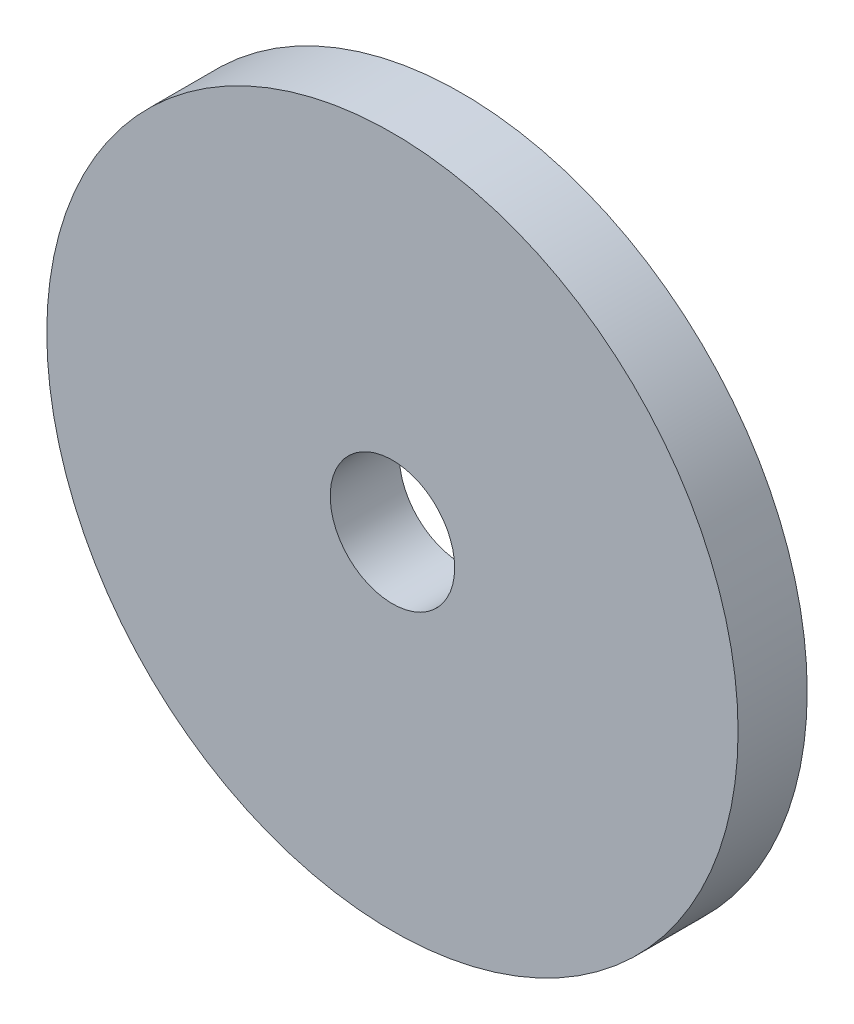
SolidWorks part; units mm, degrees
material "AISI 316 Нержавеющая сталь, лист (SS)"
ref_plane "Спереди" through (0, 0, 0) normal (0, 0, 1) x (1, 0, 0)
ref_plane "Сверху" through (0, 0, 0) normal (0, 1, 0) x (1, 0, 0)
ref_plane "Справа" through (0, 0, 0) normal (1, 0, 0) x (0, 0, -1)
sketch "Эскиз1" plane through (0, 0, 0) normal (0, 0, 1) x (1, 0, 0)
  circle A0 centre (0, 0) radius 25
  circle A1 centre (0, 0) radius 4.5
  dimension "D1" = 50
  dimension "D2" = 9
extrude "Бобышка-Вытянуть1" add sketch "Эскиз1" along normal blind 5
